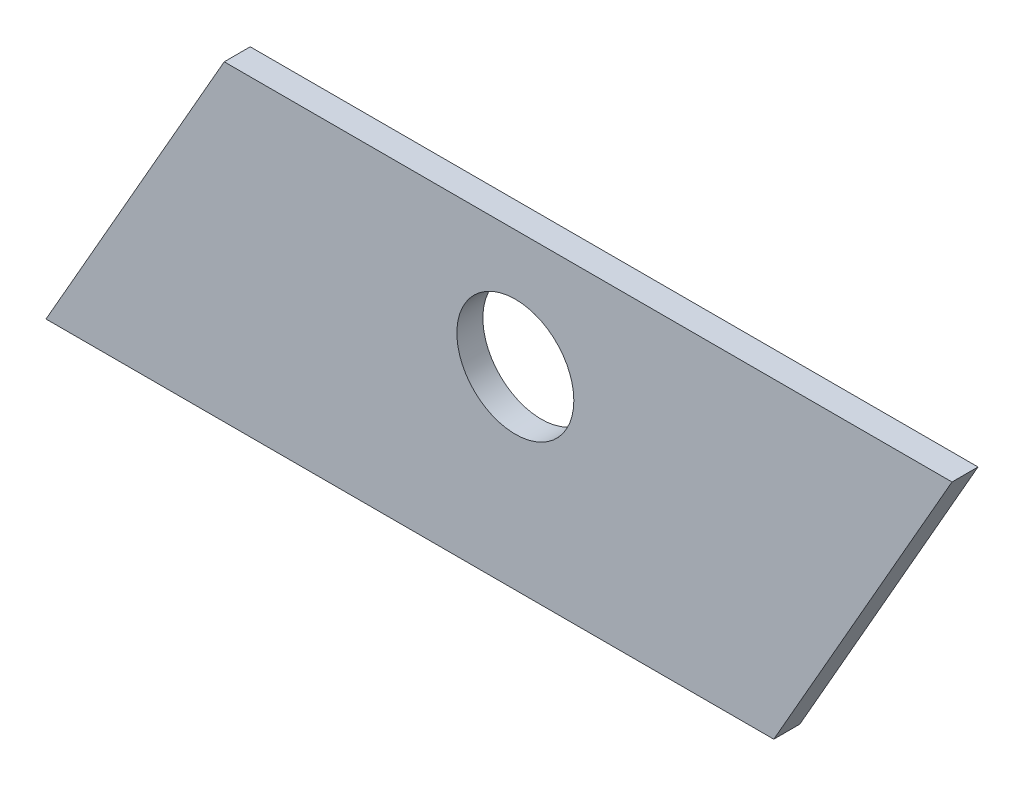
SolidWorks part; units mm, degrees
ref_plane "Front Plane" through (0, 0, 0) normal (0, 0, 1) x (1, 0, 0)
ref_plane "Top Plane" through (0, 0, 0) normal (0, 1, 0) x (1, 0, 0)
ref_plane "Right Plane" through (0, 0, 0) normal (1, 0, 0) x (0, 0, -1)
sketch "Sketch1" plane through (0, 0, 0) normal (0, 0, 1) x (1, 0, 0)
  line L0 (-88.9, -43.0893) -> (88.9, -43.0893)
  line L1 (88.9, -43.0893) -> (132.4429, 33.1107)
  line L2 (132.4429, 33.1107) -> (-45.3571, 33.1107)
  line L3 (-45.3571, 33.1107) -> (-88.9, -43.0893)
  point P2 (0, -43.0893)
  dimension "D1" = 76.2
  dimension "D2" = 177.8
extrude "Boss-Extrude1" add sketch "Sketch1" along normal mid plane 6.35
sketch "Sketch3" plane through (0, 0, 3.175) normal (0, 0, 1) x (1, 0, 0)
  line L3 (132.4429, 33.1107) -> (-45.3571, 33.1107) construction
  circle A0 centre (25.7629, 4.1547) radius 14.2875
  dimension "D1" = 28.575
  dimension "D3" = 28.956
  dimension "D2" = 71.12
extrude "Cut-Extrude2" cut sketch "Sketch3" against normal through all
